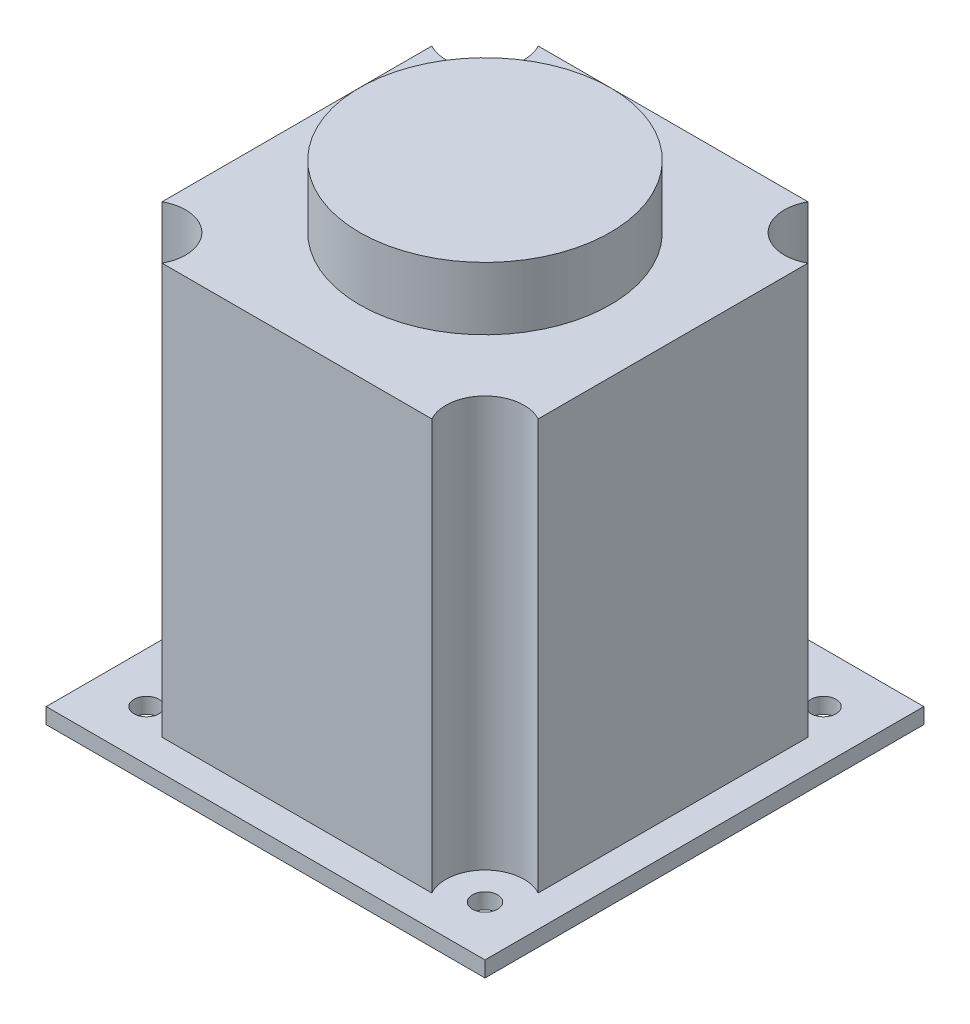
SolidWorks part; units mm, degrees
ref_plane "前视基准面" through (0, 0, 0) normal (0, 0, 1) x (1, 0, 0)
ref_plane "上视基准面" through (0, 0, 0) normal (0, 1, 0) x (1, 0, 0)
ref_plane "右视基准面" through (0, 0, 0) normal (1, 0, 0) x (0, 0, -1)
sketch "草图1" plane through (0, 0, 0) normal (0, 1, 0) x (1, 0, 0)
  line L1 (-70, -70) -> (70, -70)
  line L2 (-70, -70) -> (-70, 70)
  line L3 (-70, 70) -> (70, 70)
  line L4 (70, -70) -> (70, 70)
  line L5 (-70, -70) -> (70, 70) construction
  line L6 (-70, 70) -> (70, -70) construction
  point P0 (0, 0)
  dimension "D1" = 140
extrude "凸台-拉伸1" add sketch "草图1" along normal blind 5
sketch "草图2" plane through (0, 5, 0) normal (0, 1, 0) x (1, 0, 0)
  line L1 (-54, -54) -> (54, -54) construction
  line L2 (-54, -54) -> (-54, 54) construction
  line L3 (-54, 54) -> (54, 54) construction
  line L4 (54, -54) -> (54, 54) construction
  line L5 (-54, -54) -> (54, 54) construction
  line L6 (-54, 54) -> (54, -54) construction
  circle A0 centre (-54, 54) radius 4
  circle A1 centre (54, 54) radius 4
  circle A2 centre (54, -54) radius 4
  circle A3 centre (-54, -54) radius 4
  point P0 (0, 0)
  dimension "D2" = 8
  dimension "D1" = 108
extrude "切除-拉伸1" cut sketch "草图2" against normal blind 5
sketch "草图3" plane through (0, 5, 0) normal (0, 1, 0) x (1, 0, 0)
  circle A0 centre (0, 0) radius 7.5
  dimension "D1" = 15
extrude "凸台-拉伸2" add sketch "草图3" against normal blind 16
sketch "草图4" plane through (0, 5, 0) normal (0, 1, 0) x (1, 0, 0)
  line L1 (-43.0341, -60) -> (43.0341, -60)
  line L2 (-60, -43.0341) -> (-60, 43.0341)
  line L3 (-43.0341, 60) -> (43.0341, 60)
  line L4 (60, -43.0341) -> (60, 43.0341)
  line L5 (-54, -54) -> (54, 54) construction
  line L6 (-54, 54) -> (60, -60) construction
  arc A0 (-60, 43.0341) -> (-43.0341, 60) centre (-54, 54) ccw
  arc A1 (43.0341, 60) -> (60, 43.0341) centre (54, 54) ccw
  arc A2 (60, -43.0341) -> (43.0341, -60) centre (54, -54) ccw
  arc A3 (-43.0341, -60) -> (-60, -43.0341) centre (-54, -54) ccw
  point P0 (0, 0)
  dimension "D2" = 25
  dimension "D3" = 120
  dimension "D4" = 120
extrude "凸台-拉伸3" add sketch "草图4" along normal blind 131
sketch "草图5" plane through (0, 136, 0) normal (0, 1, 0) x (1, 0, 0)
  circle A0 centre (0, 0) radius 40
  dimension "D1" = 80
extrude "凸台-拉伸4" add sketch "草图5" along normal blind 20
